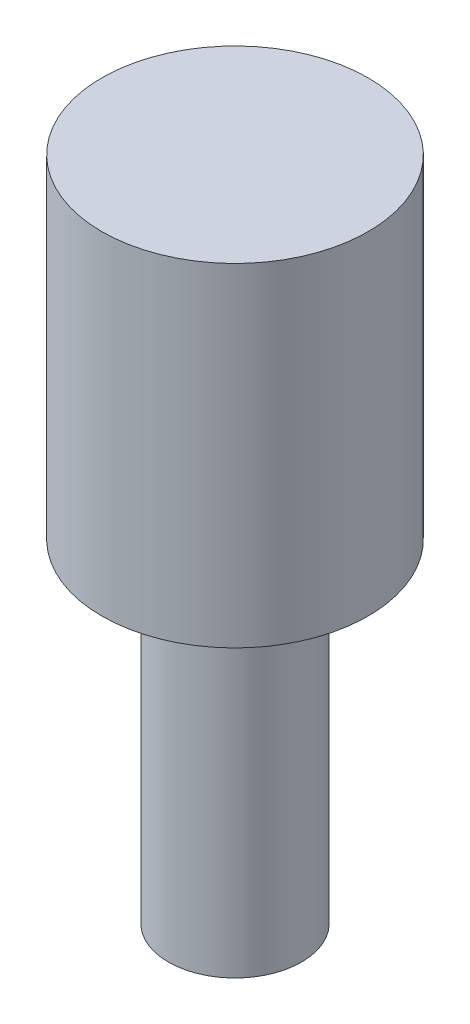
SolidWorks part; units mm, degrees
ref_plane "Plan de face" through (0, 0, 0) normal (0, 0, 1) x (1, 0, 0)
ref_plane "Plan de dessus" through (0, 0, 0) normal (0, 1, 0) x (1, 0, 0)
ref_plane "Plan de droite" through (0, 0, 0) normal (1, 0, 0) x (0, 0, -1)
sketch "Esquisse1" plane through (0, 0, 0) normal (0, 1, 0) x (1, 0, 0)
  circle A0 centre (0, 0) radius 2
  dimension "D1" = 4
extrude "Boss.-Extru.1" add sketch "Esquisse1" along normal blind 10
sketch "Esquisse2" plane through (0, 10, 0) normal (0, 1, 0) x (1, 0, 0)
  circle A2 centre (0, 0) radius 4
  circle A3 centre (0, 0) radius 4
  dimension "D1" = 2
extrude "Boss.-Extru.2" add sketch "Esquisse2" along normal blind 10
